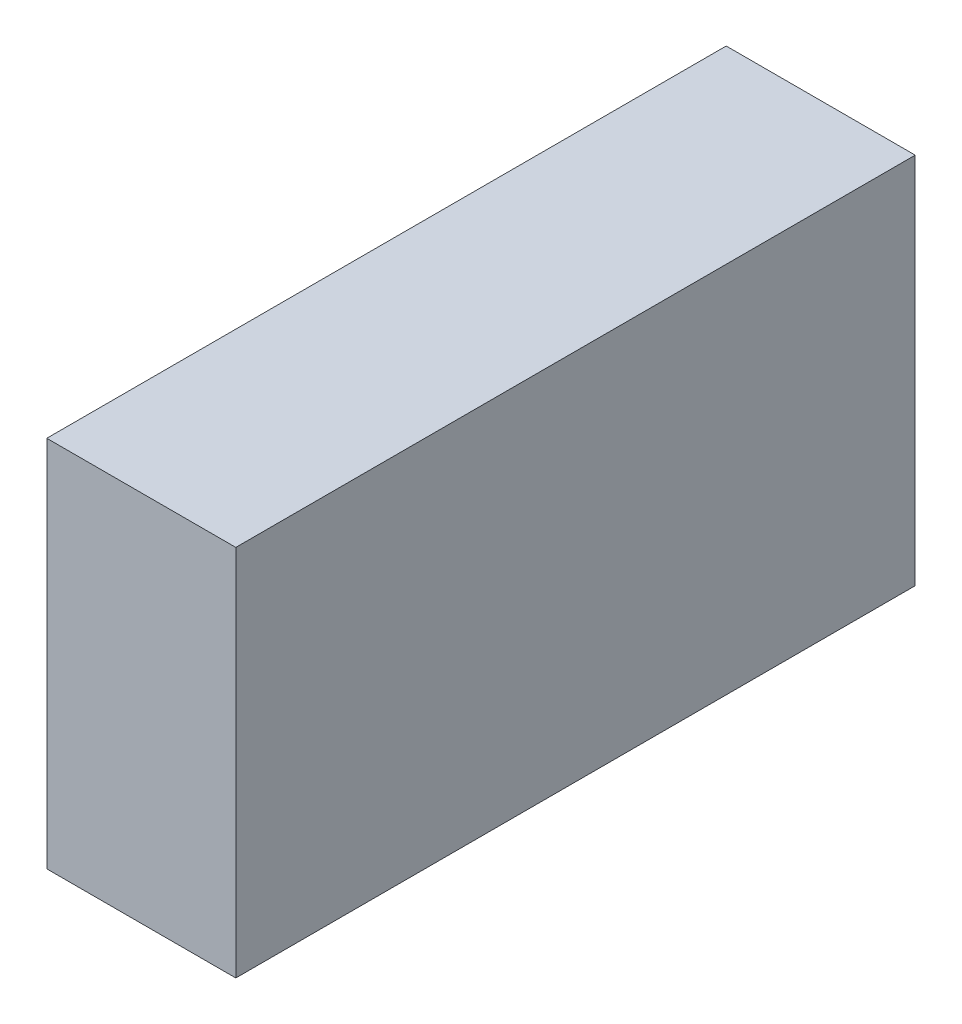
SolidWorks part; units mm, degrees
ref_plane "前视基准面" through (0, 0, 0) normal (0, 0, 1) x (1, 0, 0)
ref_plane "上视基准面" through (0, 0, 0) normal (0, 1, 0) x (1, 0, 0)
ref_plane "右视基准面" through (0, 0, 0) normal (1, 0, 0) x (0, 0, -1)
sketch "草图1" plane through (0, 0, 0) normal (1, 0, 0) x (0, 0, -1)
  line L2 (-71.3806, 65.4417) -> (-137.8806, 65.4417)
  line L3 (-71.3806, 65.4417) -> (-71.3806, 28.9417)
  line L4 (-71.3806, 28.9417) -> (-137.8806, 28.9417)
  line L5 (-137.8806, 65.4417) -> (-137.8806, 28.9417)
  dimension "D1" = 66.5
  dimension "D2" = 36.5
extrude "凸台-拉伸1" add sketch "草图1" along normal blind 18.5
